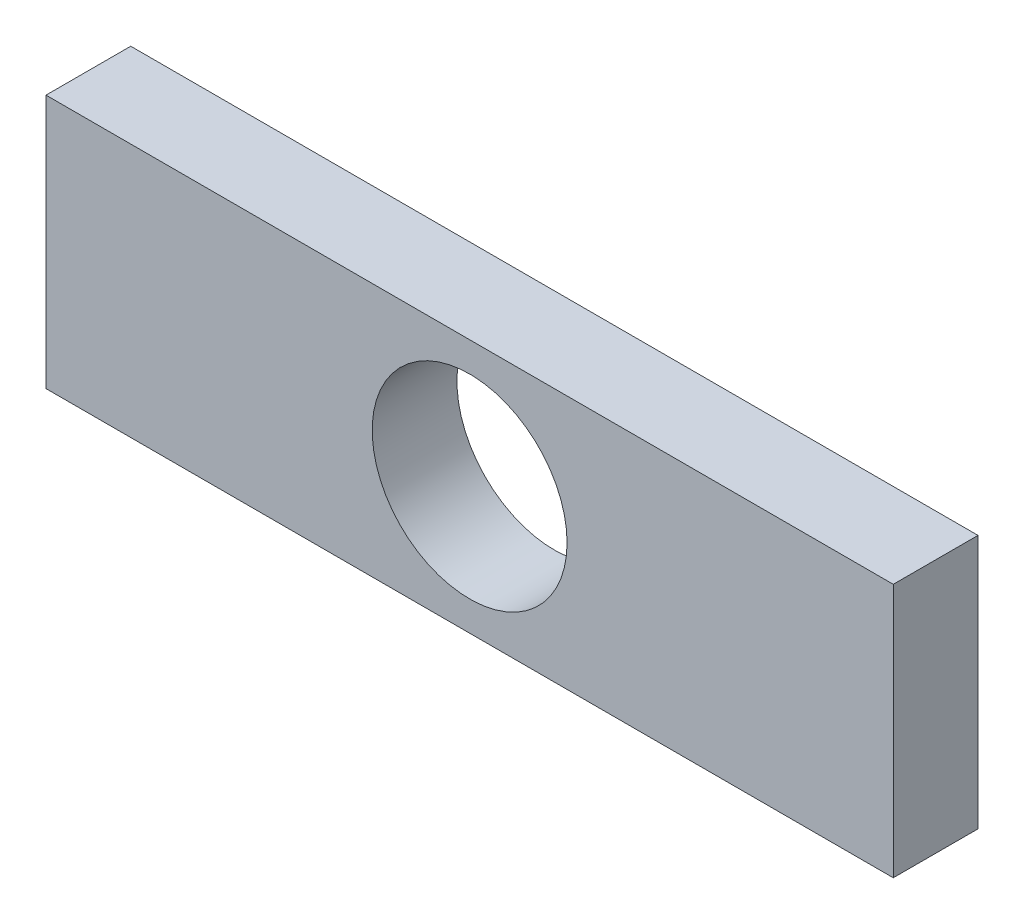
SolidWorks part; units mm, degrees
ref_plane "Front Plane" through (0, 0, 0) normal (0, 0, 1) x (1, 0, 0)
ref_plane "Top Plane" through (0, 0, 0) normal (0, 1, 0) x (1, 0, 0)
ref_plane "Right Plane" through (0, 0, 0) normal (1, 0, 0) x (0, 0, -1)
sketch "Sketch4" plane through (0, 0, 0) normal (0, 0, 1) x (1, 0, 0)
  line L0 (10, 0) -> (10, -6) construction
  line L1 (0, 0) -> (20, 0)
  line L2 (0, 0) -> (0, -6)
  line L3 (0, -6) -> (20, -6)
  line L4 (20, 0) -> (20, -6)
  line L5 (0, -3) -> (20, -3) construction
  circle A0 centre (10, -3) radius 2.3
  dimension "D3" = 4.6
  dimension "D1" = 20
  dimension "D2" = 6
extrude "Boss-Extrude2" add sketch "Sketch4" along normal blind 2
